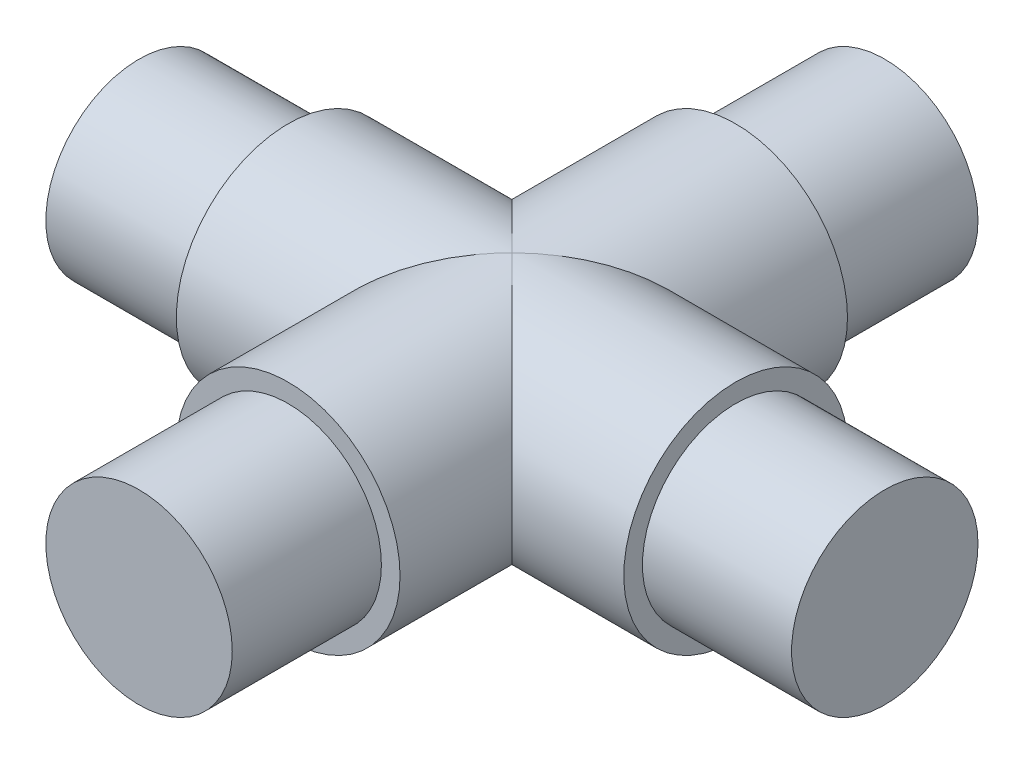
SolidWorks part; units mm, degrees
ref_plane "Front Plane" through (0, 0, 0) normal (0, 0, 1) x (1, 0, 0)
ref_plane "Top Plane" through (0, 0, 0) normal (0, 1, 0) x (1, 0, 0)
ref_plane "Right Plane" through (0, 0, 0) normal (1, 0, 0) x (0, 0, -1)
sketch "Sketch1" plane through (0, 0, 0) normal (0, 0, 1) x (1, 0, 0)
  circle A0 centre (0, 0) radius 30
  dimension "D1" = 60
extrude "Boss-Extrude1" add sketch "Sketch1" along normal mid plane 200 contours A0
sketch "Sketch2" plane through (0, 0, 100) normal (0, 0, 1) x (1, 0, 0)
  circle A0 centre (0, 0) radius 30 construction
  circle A1 centre (0, 0) radius 30
  circle A2 centre (0, 0) radius 25
  dimension "D1" = 5
extrude "Cut-Extrude1" cut sketch "Sketch2" against normal blind 40
mirror "Mirror1" about plane through (0, 0, 0) normal (0, 0, 1) of "Cut-Extrude1"
move or copy body "Body-Move/Copy1" bodies to move or copy 103 copy yes number of copies 1 rotation origin (0, 0, 0) rotation axis (0, 1, 0) rotation angle 90
combine bodies "Combine1" operation type add bodies to combine 103 105
